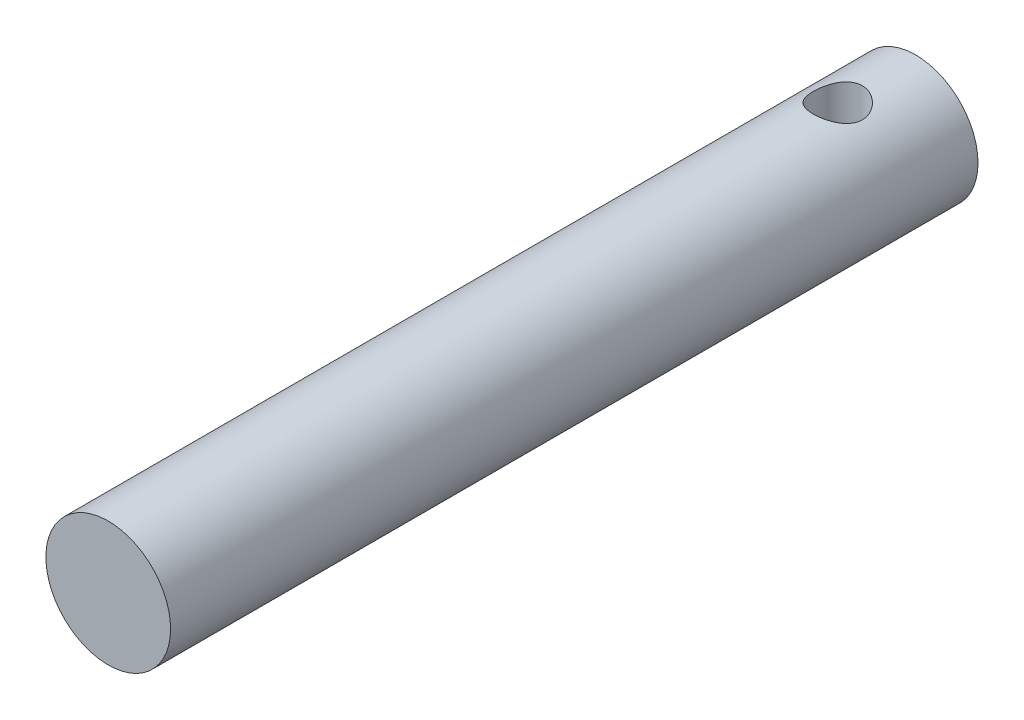
SolidWorks part; units mm, degrees
ref_plane "Plano frontal" through (0, 0, 0) normal (0, 0, 1) x (1, 0, 0)
ref_plane "Plano superior" through (0, 0, 0) normal (0, 1, 0) x (1, 0, 0)
ref_plane "Plano direito" through (0, 0, 0) normal (1, 0, 0) x (0, 0, -1)
sketch "Esboço1" plane through (0, 0, 0) normal (0, 0, 1) x (1, 0, 0)
  circle A0 centre (0, 0) radius 4
  dimension "D1" = 8
extrude "Ressalto-extrusão1" add sketch "Esboço1" along normal blind 51.8
sketch "Esboço2" plane through (0, 0, 0) normal (0, 1, 0) x (1, 0, 0)
  line L0 (4, 0) -> (-4, 0) construction
  line L1 (-4, 0) -> (-4, -51.8) construction
  circle A0 centre (0, -5) radius 1.575
  dimension "D1" = 3.15
  dimension "D2" = 5
  dimension "D3" = 4
extrude "Corte-extrusão1" cut sketch "Esboço2" against normal up to surface and the other way up to surface up to face at (4, 0, 51.8) other way up to face at (4, 0, 51.8)
